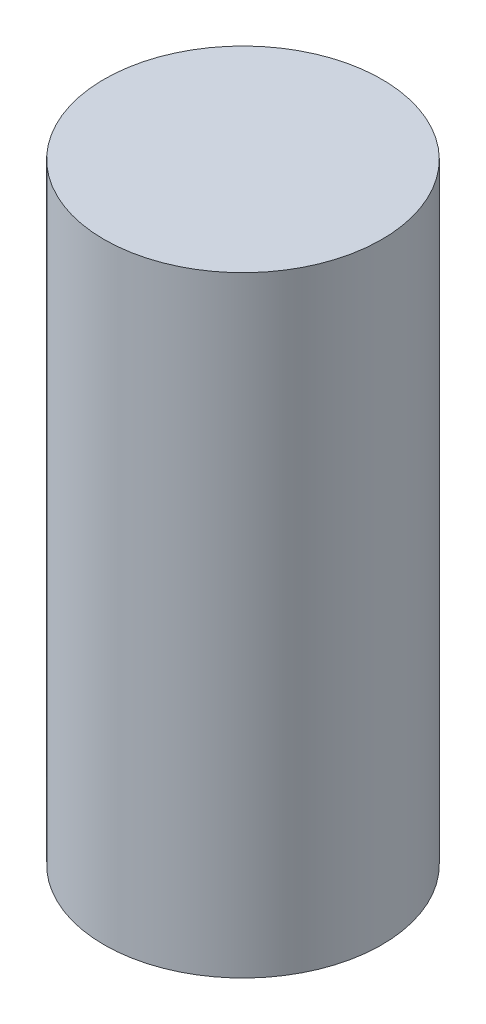
SolidWorks part; units mm, degrees
ref_plane "Front Plane" through (0, 0, 0) normal (0, 0, 1) x (1, 0, 0)
ref_plane "Top Plane" through (0, 0, 0) normal (0, 1, 0) x (1, 0, 0)
ref_plane "Right Plane" through (0, 0, 0) normal (1, 0, 0) x (0, 0, -1)
sketch "Sketch1" plane through (0, 0, 0) normal (0, 1, 0) x (1, 0, 0)
  circle A0 centre (0, 0) radius 5
  dimension "D1" = 10
extrude "Boss-Extrude1" add sketch "Sketch1" along normal mid plane 22
